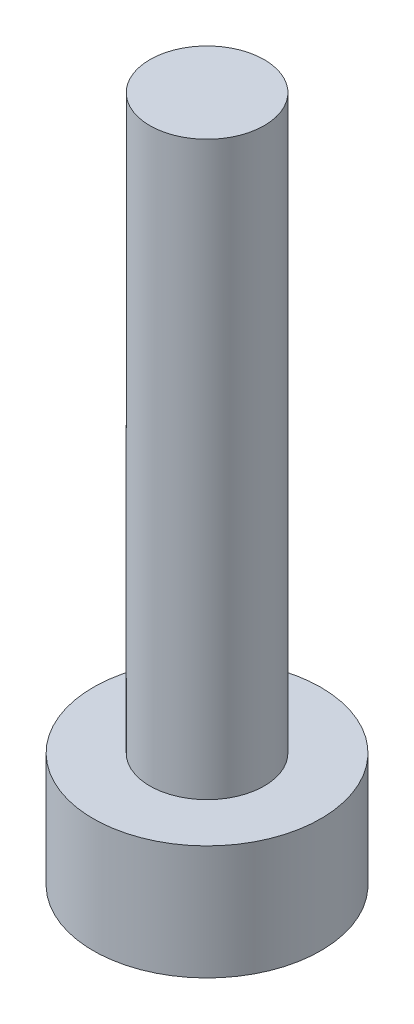
SolidWorks part; units mm, degrees
ref_plane "前视基准面" through (0, 0, 0) normal (0, 0, 1) x (1, 0, 0)
ref_plane "上视基准面" through (0, 0, 0) normal (0, 1, 0) x (1, 0, 0)
ref_plane "右视基准面" through (0, 0, 0) normal (1, 0, 0) x (0, 0, -1)
sketch "草图1" plane through (0, 0, 0) normal (0, 1, 0) x (1, 0, 0)
  circle A0 centre (0, 0) radius 1
  dimension "D1" = 2
extrude "凸台-拉伸1" add sketch "草图1" along normal blind 10
sketch "草图2" plane through (0, 0, 0) normal (0, -1, 0) x (1, 0, 0)
  circle A0 centre (0, 0) radius 1.99
  dimension "D1" = 3.98
extrude "凸台-拉伸2" add sketch "草图2" along normal blind 2
